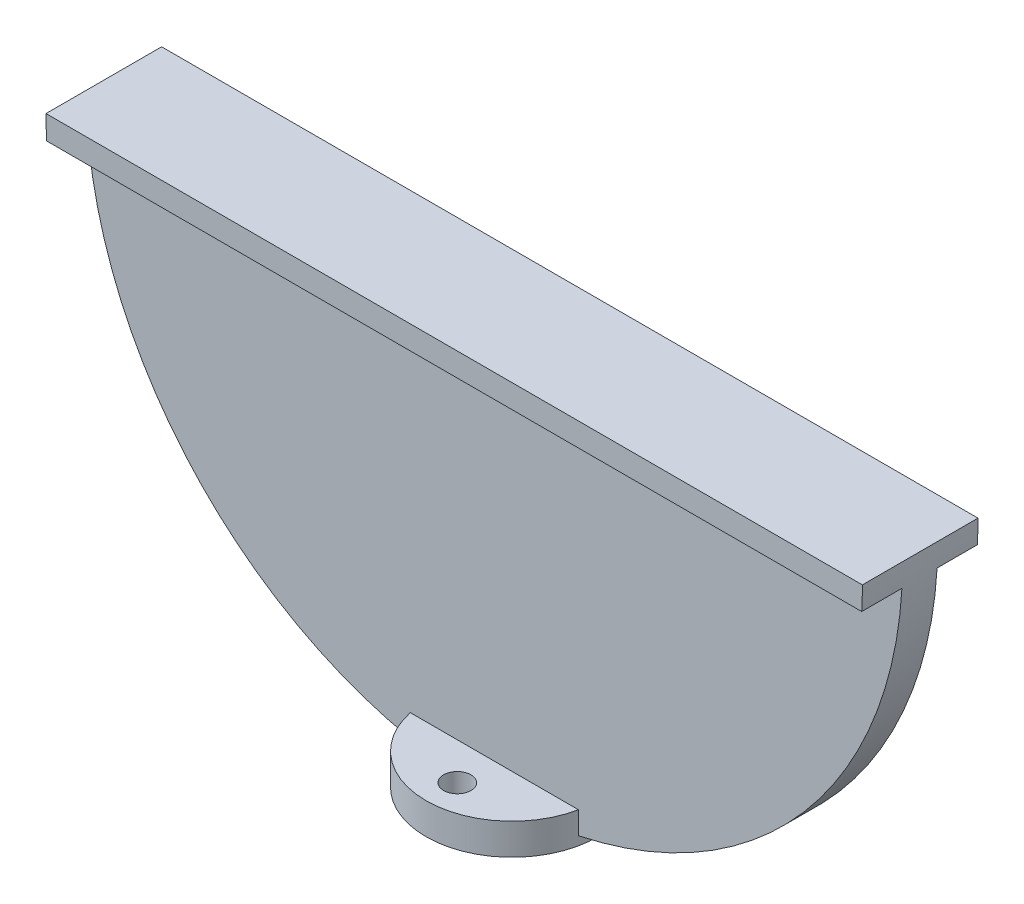
SolidWorks part; units mm, degrees
ref_plane "前视基准面" through (0, 0, 0) normal (0, 0, 1) x (1, 0, 0)
ref_plane "上视基准面" through (0, 0, 0) normal (0, 1, 0) x (1, 0, 0)
ref_plane "右视基准面" through (0, 0, 0) normal (1, 0, 0) x (0, 0, -1)
sketch "草图1" plane through (0, 0, 0) normal (0, 0, 1) x (1, 0, 0)
  line L0 (-52.25, 0) -> (52.25, 0)
  arc A0 (-52.25, 0) -> (52.25, 0) centre (0, 0) ccw
  dimension "D1" = 52.25
extrude "凸台-拉伸1" add sketch "草图1" along normal blind 4.5
ref_plane "基准面1" through (0, 0, 2.25) normal (0, 0, 1) x (1, 0, 0)
sketch "草图2" plane through (0, 0, 2.25) normal (0, 0, 1) x (1, 0, 0)
  line L1 (-52.25, 0) -> (52.25, 0)
  line L3 (-52.1638, -3) -> (52.1638, -3)
  arc A0 (-52.25, 0) -> (52.25, 0) centre (0, 0) ccw construction
  arc A1 (-52.25, 0) -> (-52.1638, -3) centre (0, 0) ccw
  arc A2 (52.1638, -3) -> (52.25, 0) centre (0, 0) ccw
  dimension "D1" = 3
extrude "凸台-拉伸2" add sketch "草图2" along normal mid plane 14.8
ref_plane "基准面2" through (0, -52.25, 0) normal (0, 1, 0) x (1, 0, 0)
sketch "草图3" plane through (0, -52.25, 0) normal (0, 1, 0) x (1, 0, 0)
  line L0 (-25.9207, -2.25) -> (25.9207, -2.25) construction
  circle A0 centre (0, -2.25) radius 11
  dimension "D1" = 22
extrude "凸台-拉伸3" add sketch "草图3" along normal blind 4
sketch "草图7" plane through (0, -52.25, 0) normal (0, -1, 0) x (1, 0, 0)
  line L0 (25.9207, 2.25) -> (-25.9207, 2.25) construction
  circle A0 centre (0, 9.25) radius 1.75
  circle A1 centre (0, -4.75) radius 1.75
  dimension "D1" = 3.5
  dimension "D2" = 7
  dimension "D3" = 14
extrude "切除-拉伸2" cut sketch "草图7" against normal up to next
